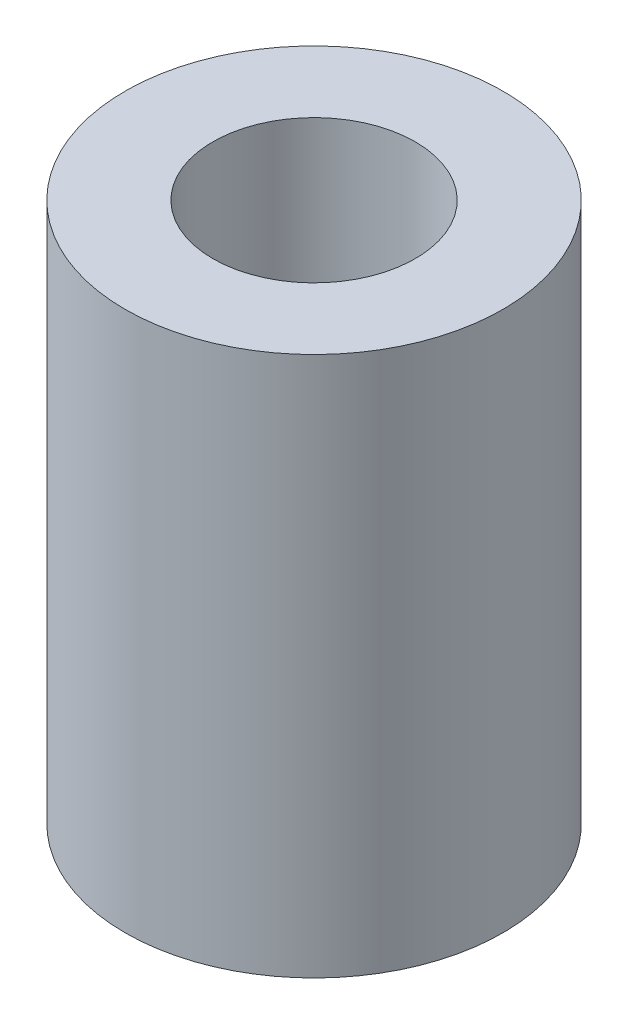
SolidWorks part; units mm, degrees
ref_plane "Front" through (0, 0, 0) normal (0, 0, 1) x (1, 0, 0)
ref_plane "Top" through (0, 0, 0) normal (0, 1, 0) x (1, 0, 0)
ref_plane "Right" through (0, 0, 0) normal (1, 0, 0) x (0, 0, -1)
sketch "Croquis1" plane through (0, 0, 0) normal (0, 1, 0) x (1, 0, 0)
  circle A0 centre (0, 0) radius 3.5
  circle A1 centre (0, 0) radius 1.875
  dimension "D1" = 7
  dimension "D2" = 3.75
extrude "Saliente-Extruir1" add sketch "Croquis1" along normal blind 10
